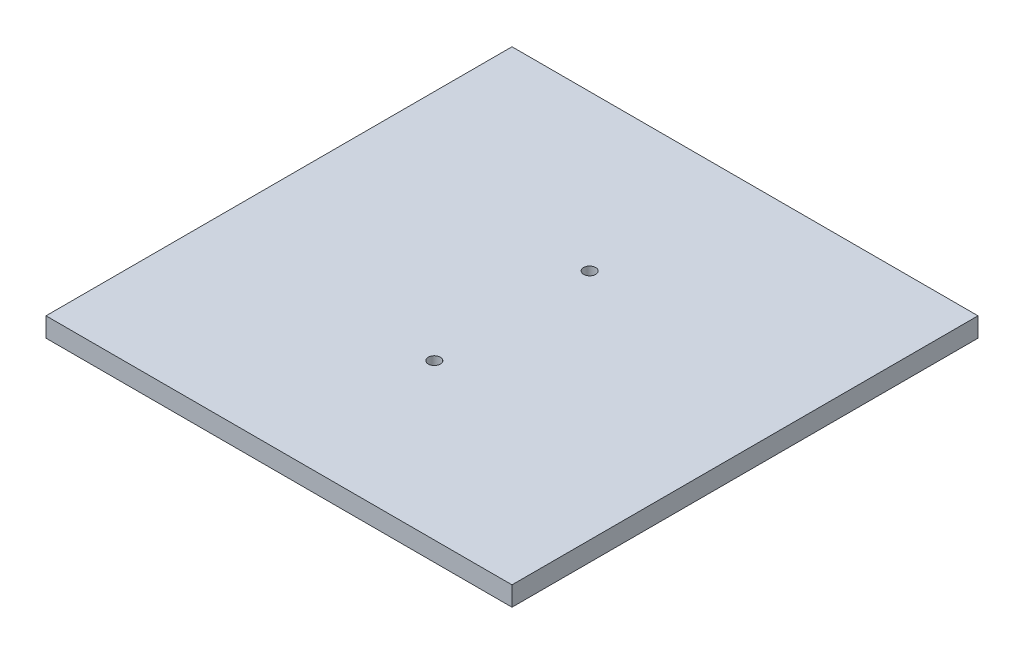
SolidWorks part; units mm, degrees
ref_plane "Piano frontale" through (0, 0, 0) normal (0, 0, 1) x (1, 0, 0)
ref_plane "Piano superiore" through (0, 0, 0) normal (0, 1, 0) x (1, 0, 0)
ref_plane "Piano destro" through (0, 0, 0) normal (1, 0, 0) x (0, 0, -1)
sketch "Schizzo1" plane through (0, 0, 0) normal (0, 1, 0) x (1, 0, 0)
  line L1 (-47.6798, -40.232) -> (72.3202, -40.232)
  line L2 (-47.6798, -40.232) -> (-47.6798, 79.768)
  line L3 (-47.6798, 79.768) -> (72.3202, 79.768)
  line L4 (72.3202, -40.232) -> (72.3202, 79.768)
  dimension "D1" = 120
  dimension "D2" = 120
extrude "Estrusione-Estrusione1" add sketch "Schizzo1" along normal blind 5
sketch "Schizzo2" plane through (0, 0, 0) normal (0, -1, 0) x (1, 0, 0)
  line L0 (12.3202, -79.768) -> (12.3202, 40.232) construction
  line L3 (72.3202, -79.768) -> (-47.6798, -79.768) construction
  line L5 (-47.6798, 40.232) -> (72.3202, 40.232) construction
  line L6 (12.3202, -19.768) -> (72.3202, -19.768) construction
  line L7 (72.3202, 40.232) -> (72.3202, -79.768) construction
  point P6 (12.3202, 0.232)
  point P12 (12.3202, -39.768)
  point P13 (0, 0)
  point P15 (0, 0)
  point P16 (-73.7744, 52.4306)
  dimension "D1" = 20
  dimension "D2" = 20
hole_wizard "Foro per Vite M2.5-1" positions "Schizzo3D1" profile "Schizzo7" hole size "M2.5" standard "IS" end condition through all
sketch3d "Schizzo3D1"
  point P0 (12.3202, 0, 0.232)
  point P3 (12.3202, 0, -39.768)
sketch "Schizzo7" plane through (12.3202, 0, 0.232) normal (1, 0, 0) x (0, 0, -1)
  line L0 (0, 0) -> (0, 5)
  line L1 (0, 5) -> (1.55, 5)
  line L2 (1.55, 5) -> (1.55, 0)
  line L5 (1.55, 0) -> (0, 0)
  line L11 (0, -6.35) -> (0, 107.95) construction
  dimension "Thru Hole Dia." = 3.1
  dimension "Thru Hole Depth" = 5
